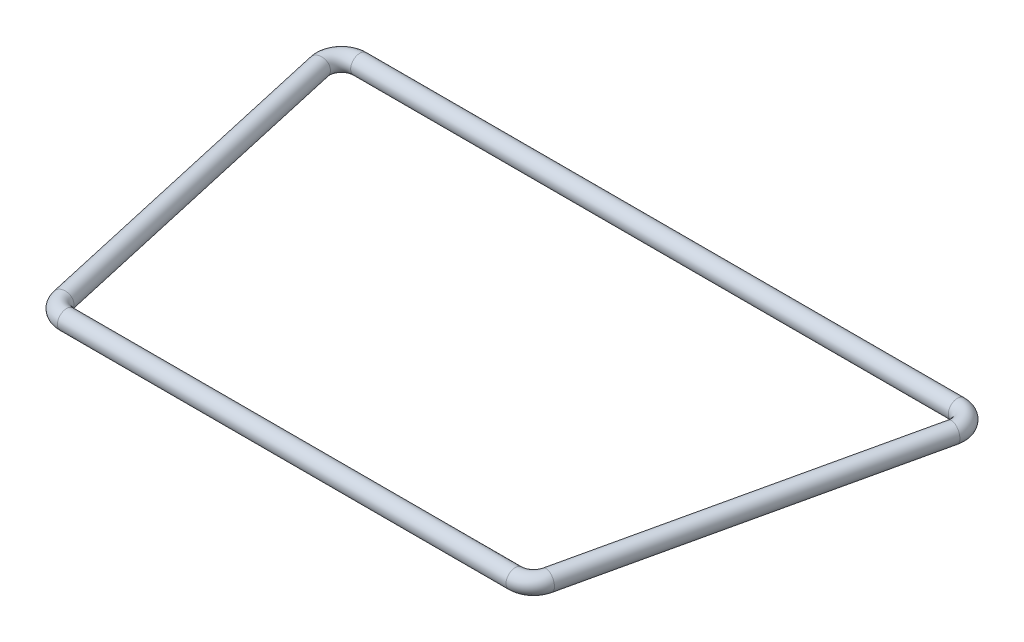
SolidWorks part; units mm, degrees
material "1060 Alloy"
ref_plane "Front Plane" through (0, 0, 0) normal (0, 0, 1) x (1, 0, 0)
ref_plane "Top Plane" through (0, 0, 0) normal (0, 1, 0) x (1, 0, 0)
ref_plane "Right Plane" through (0, 0, 0) normal (1, 0, 0) x (0, 0, -1)
sketch "Sketch1" plane through (0, 0, 0) normal (0, 1, 0) x (1, 0, 0)
  line L0 (0, 0) -> (0, 50.8) construction
  line L1 (-41.275, 50.8) -> (41.275, 50.8)
  line L2 (43.753, 47.7024) -> (33.466, 1.9824)
  line L3 (30.988, 0) -> (-30.988, 0)
  line L4 (-43.753, 47.7024) -> (-33.466, 1.9824)
  arc A0 (43.753, 47.7024) -> (41.275, 50.8) centre (41.275, 48.26) ccw
  arc A1 (33.466, 1.9824) -> (30.988, 0) centre (30.988, 2.54) cw
  arc A2 (-30.988, 0) -> (-33.466, 1.9824) centre (-30.988, 2.54) cw
  arc A3 (-43.753, 47.7024) -> (-41.275, 50.8) centre (-41.275, 48.26) cw
  point P9 (44.45, 50.8)
  point P12 (33.02, 0)
  point P15 (-33.02, 0)
  point P18 (-44.45, 50.8)
  dimension "D4" = 2.54
  dimension "D1" = 88.9
  dimension "D2" = 66.04
  dimension "D3" = 50.8
sweep "Sweep1" add path "Sketch1" circular profile diameter 2.54 parameters "D3"=2.54
